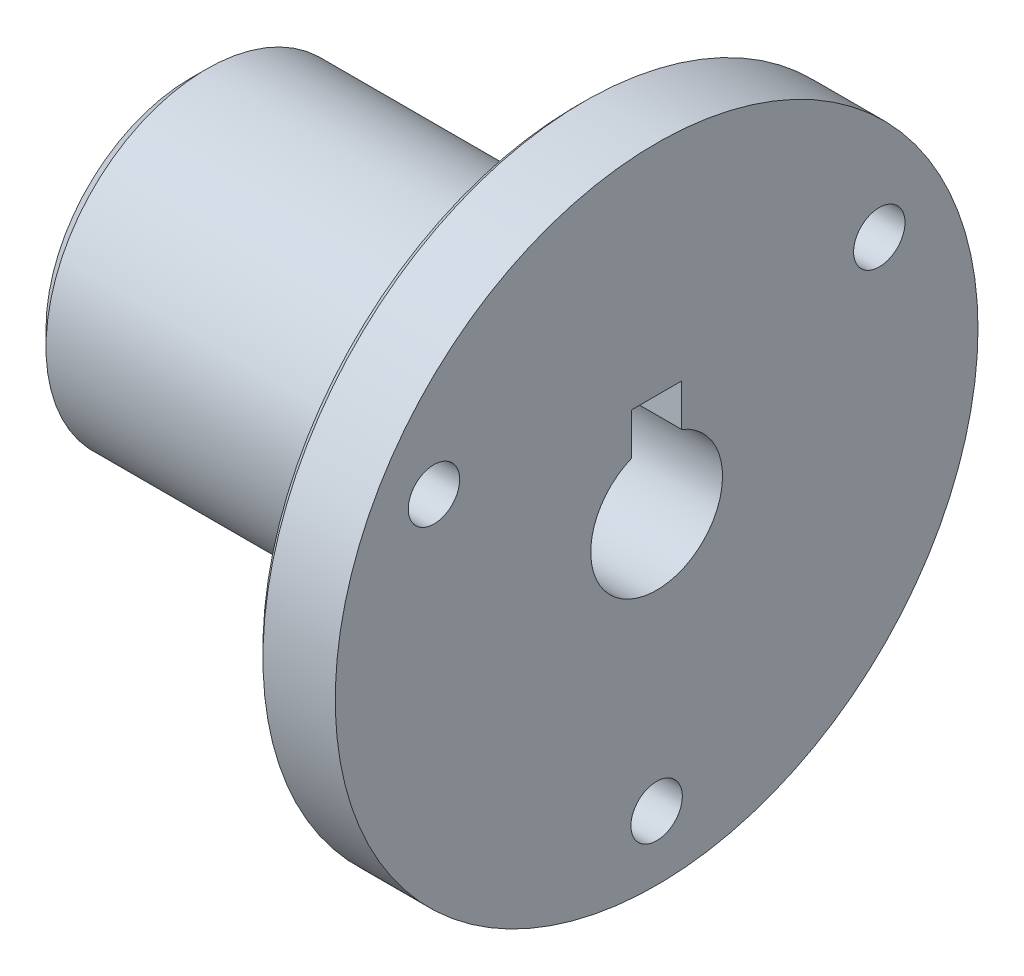
SolidWorks part; units mm, degrees
ref_plane "Front" through (0, 0, 0) normal (0, 0, 1) x (1, 0, 0)
ref_plane "Top" through (0, 0, 0) normal (0, 1, 0) x (1, 0, 0)
ref_plane "Right" through (0, 0, 0) normal (1, 0, 0) x (0, 0, -1)
sketch "草图1" plane through (0, 0, 0) normal (1, 0, 0) x (0, 0, -1)
  line L0 (0, 6.4) -> (-1.55, 6.4)
  line L5 (0, 6.4) -> (1.55, 6.4)
  line L6 (-1.55, 6.4) -> (-1.55, 3.7957)
  line L7 (0, 0) -> (0, 6.4) construction
  line L8 (1.55, 6.4) -> (1.55, 3.7957)
  circle A1 centre (0, 0) radius 10
  arc A2 (-1.55, 3.7957) -> (1.55, 3.7957) centre (0, 0) ccw
  dimension "D2" = 20
extrude "凸台-拉伸1" add sketch "草图1" along normal blind 24
sketch "草图2" plane through (24, 0, 0) normal (1, 0, 0) x (0, 0, -1)
  line L0 (0, 0) -> (13.8564, 8) construction
  line L1 (0, 0) -> (-13.8564, 8) construction
  line L2 (0, 0) -> (0, -16) construction
  circle A0 centre (0, 0) radius 16 construction
  circle A1 centre (0, 0) radius 20
  circle A2 centre (-13.8564, 8) radius 1.6
  circle A3 centre (13.8564, 8) radius 1.6
  circle A4 centre (0, -16) radius 1.6
extrude "凸台-拉伸2" add sketch "草图2" along normal blind 5
chamfer "倒角1" distance 0.5 angle 45 1 edges at (0, -4.1, 0)
chamfer "倒角2" distance 1 angle 45 1 edges at (0, 0, -10)
chamfer "倒角3" distance 0.5 angle 45 1 edges at (24, 0, -20)
chamfer "倒角4" distance 2 angle 45 1 edges at (24, 0, -10)
sketch "草图3" plane through (24, 0, 0) normal (-1, 0, 0) x (0, 0, 1)
  line L0 (0, 0) -> (0, 6.4) construction
  line L1 (-1.55, 6.4) -> (1.55, 6.4) construction
  line L2 (0, 6.4) -> (-1.55, 6.4)
  line L3 (-1.55, 6.4) -> (-1.55, 3.7957)
  line L4 (0, 6.4) -> (1.55, 6.4)
  line L5 (1.55, 6.4) -> (1.55, 3.7957)
  arc A0 (-1.55, 3.7957) -> (1.55, 3.7957) centre (0, 0) ccw
extrude "切除-拉伸1" cut sketch "草图3" against normal blind 10
